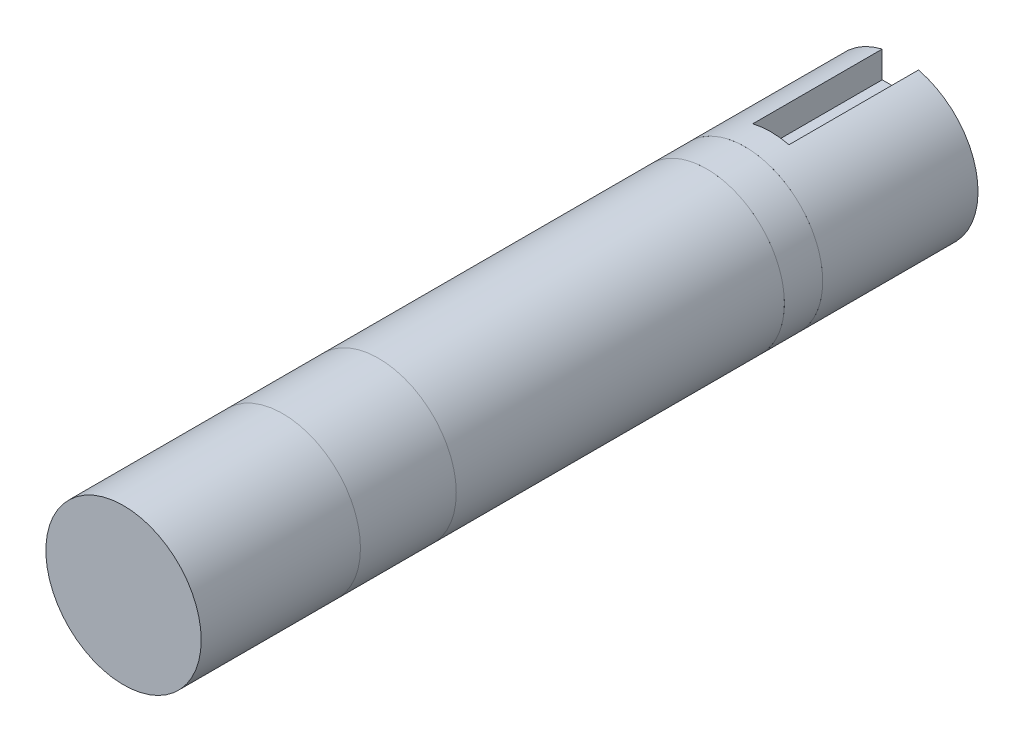
SolidWorks part; units mm, degrees
material "1023 Carbon Steel Sheet (SS)"
ref_plane "Front Plane" through (0, 0, 0) normal (0, 0, 1) x (1, 0, 0)
ref_plane "Top Plane" through (0, 0, 0) normal (0, 1, 0) x (1, 0, 0)
ref_plane "Right Plane" through (0, 0, 0) normal (1, 0, 0) x (0, 0, -1)
sketch "Sketch1" plane through (0, 0, 0) normal (0, 0, 1) x (1, 0, 0)
  circle A0 centre (0, 0) radius 150
  dimension "D1" = 300
extrude "Boss-Extrude1" add sketch "Sketch1" against normal blind 1500
sketch "Sketch3" plane through (0, 0, -1500) normal (0, 0, -1) x (-1, 0, 0)
  line L1 (-35, 94.4) -> (35, 94.4)
  line L2 (-35, 94.4) -> (-35, 164.4)
  line L3 (-35, 164.4) -> (35, 164.4)
  line L4 (35, 94.4) -> (35, 164.4)
  line L5 (-35, 94.4) -> (35, 164.4) construction
  line L6 (-35, 164.4) -> (35, 94.4) construction
  point P0 (0, 129.4)
  dimension "D1" = 70
  dimension "D2" = 164.4
extrude "Cut-Extrude2" cut sketch "Sketch3" against normal blind 250
ref_plane "Plane1" through (0, 0, 0) normal (0, 1, 0) x (1, 0, 0)
ref_plane "Plane3" through (0, 0, -400) normal (0, 0, 1) x (1, 0, 0)
sketch "Sketch7" plane through (0, 0, -400) normal (0, 0, 1) x (1, 0, 0)
  circle A0 centre (0, 0) radius 150
  dimension "D1" = 300
extrude "Extrude-Thin1" add sketch "Sketch7" against normal mid plane 185 thin thin type one direction wall 0.0001
ref_plane "Plane4" through (0, 0, -1200) normal (0, 0, -1) x (-1, 0, 0)
sketch "Sketch8" plane through (0, 0, -1200) normal (0, 0, -1) x (-1, 0, 0)
  circle A0 centre (0, 0) radius 150
  dimension "D1" = 300
extrude "Extrude-Thin2" add sketch "Sketch8" against normal blind 74 thin thin type one direction wall 0.0001
